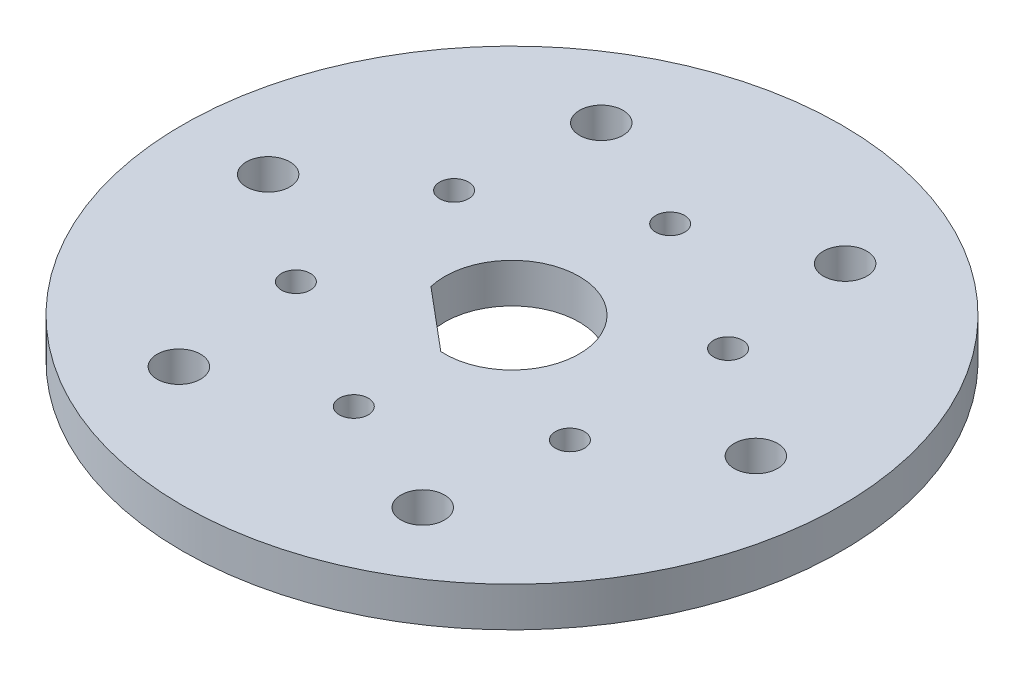
SolidWorks part; units mm, degrees
ref_plane "前视基准面" through (0, 0, 0) normal (0, 0, 1) x (1, 0, 0)
ref_plane "上视基准面" through (0, 0, 0) normal (0, 1, 0) x (1, 0, 0)
ref_plane "右视基准面" through (0, 0, 0) normal (1, 0, 0) x (0, 0, -1)
other "Configuration Table"
sketch "草图1" plane through (0, 0, 0) normal (0, 1, 0) x (1, 0, 0)
  line L5 (-4.959, -1.1911) -> (-0.3119, -5.0905)
  circle A0 centre (0, 12) radius 1.1
  circle A1 centre (-9.25, 16.0215) radius 1.65
  circle A3 centre (0, 0) radius 25
  circle A4 centre (9.25, 16.0215) radius 1.65
  circle A5 centre (10.3923, 6) radius 1.1
  circle A6 centre (18.5, 0) radius 1.65
  circle A7 centre (10.3923, -6) radius 1.1
  circle A8 centre (9.25, -16.0215) radius 1.65
  circle A9 centre (0, -12) radius 1.1
  circle A10 centre (-9.25, -16.0215) radius 1.65
  circle A11 centre (-10.3923, -6) radius 1.1
  circle A12 centre (-18.5, 0) radius 1.65
  circle A13 centre (-10.3923, 6) radius 1.1
  arc A25 (-0.3119, -5.0905) -> (-4.959, -1.1911) centre (0, 0) ccw
  point P29 (0, 0)
extrude "凸台-拉伸1" add sketch "草图1" along normal blind 3
